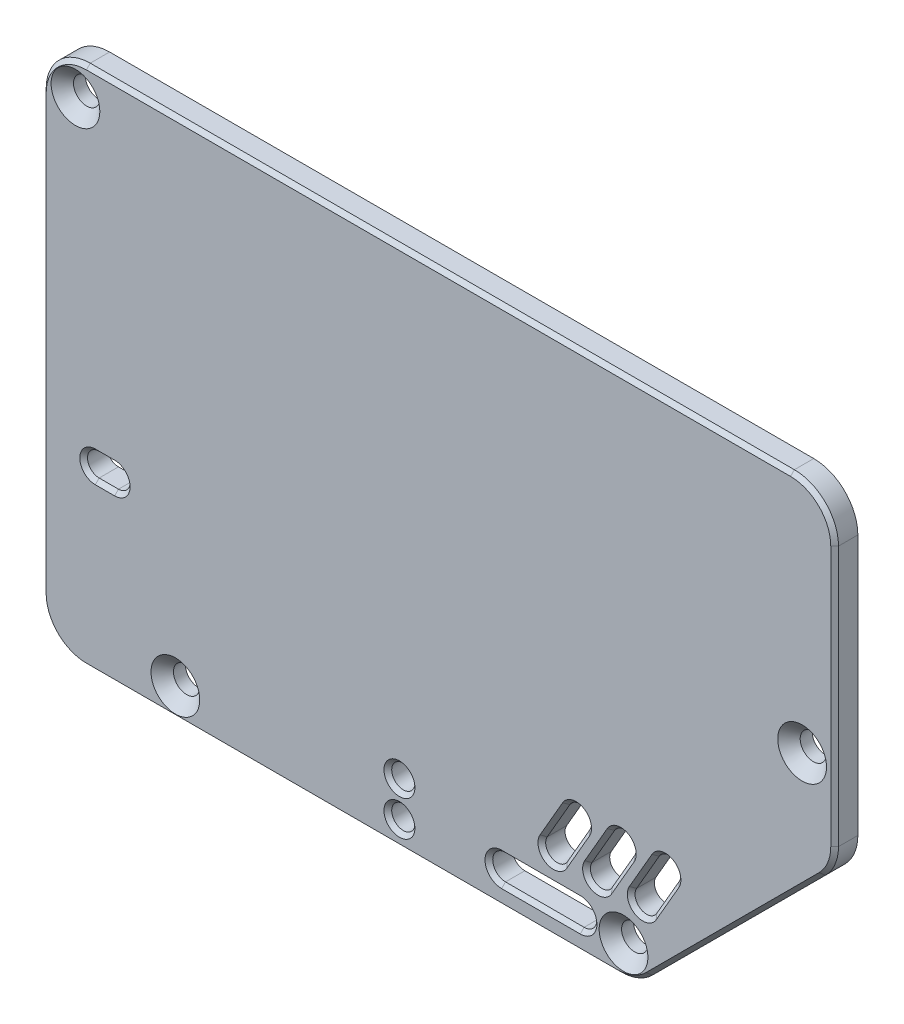
SolidWorks part; units mm, degrees
ref_plane "Front Plane" through (0, 0, 0) normal (0, 0, 1) x (1, 0, 0)
ref_plane "Top Plane" through (0, 0, 0) normal (0, 1, 0) x (1, 0, 0)
ref_plane "Right Plane" through (0, 0, 0) normal (1, 0, 0) x (0, 0, -1)
sketch "Sketch2" plane through (0, 0, 8.62) normal (0, 0, 1) x (1, 0, 0)
  line L0 (4.5, 66.2) -> (95.5, 66.2)
  line L1 (101.2, 60.5) -> (101.2, 26.864)
  line L2 (99.5305, 22.8335) -> (77.1665, 0.4695)
  line L3 (73.136, -1.2) -> (4.5, -1.2)
  line L4 (-1.2, 4.5) -> (-1.2, 60.5)
  line L5 (-1.5, 60.5) -> (-1.5, 4.5) construction
  arc A0 (4.5, -1.2) -> (-1.2, 4.5) centre (4.5, 4.5) cw
  arc A1 (77.1665, 0.4695) -> (73.136, -1.2) centre (73.136, 4.5) cw
  arc A2 (101.2, 26.864) -> (99.5305, 22.8335) centre (95.5, 26.864) cw
  arc A3 (95.5, 66.2) -> (101.2, 60.5) centre (95.5, 60.5) cw
  arc A4 (4.5, 66.2) -> (-1.2, 60.5) centre (4.5, 60.5) ccw
  arc A5 (-1.5, 4.5) -> (4.5, -1.5) centre (4.5, 4.5) ccw construction
  arc A6 (4.5, 66.5) -> (-1.5, 60.5) centre (4.5, 60.5) ccw construction
  arc A7 (101.5, 60.5) -> (95.5, 66.5) centre (95.5, 60.5) ccw construction
  arc A8 (73.136, -1.5) -> (77.3787, 0.2574) centre (73.136, 4.5) ccw construction
  circle A9 centre (3.0858, 61.9142) radius 1.5 construction
  circle A10 centre (16, 2.5) radius 1.5 construction
  circle A11 centre (73.9175, 2.659) radius 1.5 construction
  circle A12 centre (97, 35.5) radius 1.5 construction
  circle A13 centre (16, 2.5) radius 1.35 construction
  arc A14 (101.3205, 25.4074) -> (101.5, 26.864) centre (95.5, 26.864) ccw construction
  circle A15 centre (73.9175, 2.659) radius 1.35 construction
  circle A16 centre (97, 35.5) radius 1.35 construction
  circle A17 centre (3.0858, 61.9142) radius 1.35 construction
  dimension "D1" = 0.3
  dimension "D2" = 3
extrude "Boss-Extrude1" add sketch "Sketch2" along normal blind 3
hole_wizard "CSK for M3 Flat Head Machine Screw1" positions "Sketch4" profile "Sketch5" countersink size "M3" standard "ANSI Metric" end condition through all
sketch "Sketch4" plane through (0, 0, 11.62) normal (0, 0, 1) x (1, 0, 0)
  point P0 (3.0858, 61.9142)
  point P3 (16, 2.5)
  point P6 (73.9175, 2.659)
  point P9 (97, 35.5)
sketch "Sketch5" plane through (3.0858, 61.9142, 11.62) normal (1, 0, 0) x (0, -1, 0)
  line L0 (0, 0) -> (0, 3)
  line L1 (0, 3) -> (1.7, 3)
  line L2 (1.7, 3) -> (1.7, 1.45)
  line L3 (1.7, 1.45) -> (3.15, 0)
  line L5 (3.15, 0) -> (0, 0)
  line L6 (-1.7, 1.45) -> (-3.15, 0) construction
  line L11 (0, -6.35) -> (0, 107.95) construction
  dimension "Thru Hole Dia." = 3.4
  dimension "Thru Hole Depth" = 3
  dimension "Near C'Sink Dia." = 6.3
  dimension "Near C'Sink Angle" = 90
sketch "Sketch6" plane through (0, 0, 11.62) normal (0, 0, 1) x (1, 0, 0)
  line L6 (72.0938, 16.422) -> (72.0938, 14.1605) construction
  line L8 (78.5938, 16.422) -> (65.5938, 16.422) construction
  line L10 (68.326, 3.048) -> (58.166, 3.048) construction
  line L11 (68.326, 1.397) -> (58.166, 1.397)
  line L12 (68.326, 4.699) -> (58.166, 4.699)
  line L13 (72.0938, 7.6835) -> (72.0938, 5.422) construction
  line L14 (65.5938, 5.422) -> (78.5938, 5.422) construction
  arc A4 (68.326, 1.397) -> (68.326, 4.699) centre (68.326, 3.048) ccw
  arc A5 (58.166, 4.699) -> (58.166, 1.397) centre (58.166, 3.048) ccw
  point P26 (63.246, 3.048)
  dimension "D4" = 3.302
extrude "Cut-Extrude1" cut sketch "Sketch6" against normal through all
sketch "Sketch7" plane through (0, 0, 11.62) normal (0, 0, 1) x (1, 0, 0)
  line L1 (19.25, 57.135) -> (67.25, 57.135)
  line L2 (18.615, 56.5) -> (18.615, 20.1)
  line L3 (19.25, 19.465) -> (67.25, 19.465)
  line L4 (67.885, 56.5) -> (67.885, 20.1)
  arc A4 (67.25, 57.135) -> (67.885, 56.5) centre (67.25, 56.5) cw
  arc A5 (67.25, 19.465) -> (67.885, 20.1) centre (67.25, 20.1) ccw
  arc A6 (18.615, 20.1) -> (19.25, 19.465) centre (19.25, 20.1) ccw
  arc A7 (19.25, 57.135) -> (18.615, 56.5) centre (19.25, 56.5) ccw
  dimension "D2" = 0.635
split line "Split Line1" [suppressed]
sketch "Sketch8" plane through (0, 0, 11.62) normal (0, 0, 1) x (1, 0, 0)
  circle A0 centre (44.958, 2.54) radius 1
  circle A1 centre (44.958, 6.096) radius 1
  dimension "D1" = 2
extrude "Cut-Extrude2" cut sketch "Sketch8" against normal blind 10
sketch "Sketch9" plane through (0, 0, 11.62) normal (0, 0, 1) x (1, 0, 0)
  line L0 (65.0938, 10.922) -> (68.5938, 10.922) construction
  line L1 (68.5938, 10.922) -> (72.0938, 10.922) construction
  line L2 (72.0938, 10.922) -> (75.5938, 10.922) construction
  line L3 (75.5938, 10.922) -> (79.0938, 10.922) construction
  line L4 (66.8438, 13.9531) -> (66.8438, 7.8909) construction
  line L5 (65.0938, 10.922) -> (66.8438, 7.8909) construction
  line L6 (70.3438, 7.8909) -> (70.3438, 13.9531) construction
  line L7 (72.0938, 15.272) -> (72.0938, 6.572) construction
  line L8 (73.8438, 13.9531) -> (73.8438, 7.8909) construction
  line L9 (75.8938, 15.272) -> (68.2938, 15.272) construction
  line L10 (77.3438, 7.8909) -> (77.3438, 13.9531) construction
  line L11 (68.2938, 6.572) -> (75.8938, 6.572) construction
  circle A0 centre (65.0938, 10.922) radius 1
  circle A1 centre (68.5938, 10.922) radius 1
  circle A2 centre (72.0938, 10.922) radius 1
  circle A3 centre (75.5938, 10.922) radius 1
  circle A4 centre (79.0938, 10.922) radius 1
  circle A5 centre (66.8438, 13.9531) radius 1
  circle A6 centre (70.3438, 13.9531) radius 1
  circle A7 centre (73.8438, 13.9531) radius 1
  circle A8 centre (77.3438, 13.9531) radius 1
  circle A9 centre (66.8438, 7.8909) radius 1
  circle A10 centre (70.3438, 7.8909) radius 1
  circle A11 centre (73.8438, 7.8909) radius 1
  circle A12 centre (77.3438, 7.8909) radius 1
  circle A13 centre (44.958, 6.096) radius 1 construction
  point P18 (66.8438, 10.922)
  point P19 (70.3438, 10.922)
  point P20 (73.8438, 10.922)
  point P21 (77.3438, 10.922)
  dimension "D1" = 3.5
extrude "Cut-Extrude3" [suppressed] cut sketch "Sketch9" against normal blind 10
sketch "Sketch10" plane through (0, 0, 11.62) normal (0, 0, 1) x (1, 0, 0)
  line L0 (5.1479, 21.844) -> (8.6479, 21.844) construction
  line L1 (6.8979, 23.4191) -> (6.8979, 20.2689) construction
  line L2 (9.3459, 23.4191) -> (4.4498, 23.4191) construction
  line L3 (4.4498, 20.2689) -> (9.3459, 20.2689) construction
  circle A0 centre (5.1479, 21.844) radius 1
  circle A1 centre (8.6479, 21.844) radius 1
  circle A2 centre (44.958, 6.096) radius 1 construction
  point P12 (6.8979, 21.844)
  dimension "D1" = 3.5
extrude "Cut-Extrude4" cut sketch "Sketch10" against normal blind 10
chamfer "Chamfer1" [suppressed] distance 0.5 angle 45
sketch "Sketch12" plane through (0, 0, 11.62) normal (0, 0, 1) x (1, 0, 0)
  line L0 (5.6479, 21.844) -> (8.1479, 21.844) construction
  line L1 (5.6479, 23.344) -> (8.1479, 23.344)
  line L2 (5.6479, 20.344) -> (8.1479, 20.344)
  line L3 (44.958, 6.596) -> (44.958, 2.04) construction
  line L4 (42.6658, 5.096) -> (46.9218, 5.096) construction
  line L5 (46.9218, 3.54) -> (42.9064, 3.54) construction
  line L6 (70.6325, 8.3909) -> (73.5552, 13.4531) construction
  line L7 (69.3335, 9.1409) -> (72.2561, 14.2031)
  line L8 (71.9315, 7.6409) -> (74.8542, 12.7031)
  line L9 (66.658, 6.8909) -> (75.9903, 6.8909) construction
  line L10 (71.007, 14.9531) -> (76.3222, 14.9531) construction
  line L11 (64.859, 8.3909) -> (67.7817, 13.4531) construction
  line L12 (63.56, 9.1409) -> (66.4826, 14.2031)
  line L13 (66.158, 7.6409) -> (69.0807, 12.7031)
  line L14 (76.406, 8.3909) -> (79.3287, 13.4531) construction
  line L15 (75.107, 9.1409) -> (78.0296, 14.2031)
  line L16 (77.7051, 7.6409) -> (80.6277, 12.7031)
  arc A0 (5.6479, 23.344) -> (5.6479, 20.344) centre (5.6479, 21.844) ccw
  arc A1 (8.1479, 20.344) -> (8.1479, 23.344) centre (8.1479, 21.844) ccw
  circle A2 centre (5.1479, 21.844) radius 1 construction
  circle A3 centre (8.6479, 21.844) radius 1 construction
  circle A4 centre (44.958, 6.596) radius 1.5
  circle A5 centre (44.958, 2.04) radius 1.5
  circle A6 centre (73.8438, 13.9531) radius 1 construction
  circle A7 centre (44.958, 6.096) radius 1 construction
  circle A8 centre (44.958, 2.54) radius 1 construction
  arc A9 (69.3335, 9.1409) -> (71.9315, 7.6409) centre (70.6325, 8.3909) ccw
  arc A10 (74.8542, 12.7031) -> (72.2561, 14.2031) centre (73.5552, 13.4531) ccw
  arc A11 (63.56, 9.1409) -> (66.158, 7.6409) centre (64.859, 8.3909) ccw
  circle A12 centre (70.3438, 7.8909) radius 1 construction
  arc A13 (69.0807, 12.7031) -> (66.4826, 14.2031) centre (67.7817, 13.4531) ccw
  arc A14 (75.107, 9.1409) -> (77.7051, 7.6409) centre (76.406, 8.3909) ccw
  arc A15 (80.6277, 12.7031) -> (78.0296, 14.2031) centre (79.3287, 13.4531) ccw
  point P2 (6.8979, 21.844)
  point P7 (4.1479, 21.844)
  point P8 (4.1479, 21.844)
  point P11 (9.6479, 21.844)
  point P12 (9.6479, 21.844)
  point P13 (5.1479, 21.844)
  point P21 (44.958, 6.096)
  point P33 (72.0938, 10.922)
  point P50 (66.3203, 10.922)
  point P55 (77.8673, 10.922)
  dimension "D2" = 3
  dimension "D1" = 3
  dimension "D3" = 3
  dimension "D4" = 2
  dimension "D5" = 2
extrude "Cut-Extrude5" cut sketch "Sketch12" against normal blind 10
chamfer "Chamfer2" distance 0.5 angle 45 32 edges at (63.246, 1.397, 11.62) (69.977, 3.048, 11.62) (56.515, 3.048, 11.62) (63.246, 4.699, 11.62) (79.1664, 10.172, 11.62) (80.0787, 14.7521, 11.62) (75.656, 7.0919, 11.62) (76.5683, 11.672, 11.62) (73.3929, 10.172, 11.62) (74.3052, 14.7521, 11.62) (69.8825, 7.0919, 11.62) (70.7948, 11.672, 11.62) (65.0213, 11.672, 11.62) (64.109, 7.0919, 11.62) (68.5317, 14.7521, 11.62) (67.6194, 10.172, 11.62) (46.458, 2.04, 11.62) (46.458, 6.596, 11.62) (6.8979, 23.344, 11.62) (4.1479, 21.844, 11.62) (9.6479, 21.844, 11.62) (6.8979, 20.344, 11.62) (100.7661, 24.6827, 11.62) (101.2, 43.682, 11.62) (88.3485, 11.6515, 11.62) (99.5305, 64.5305, 11.62) (75.3173, -0.7661, 11.62) (50, 66.2, 11.62) (38.818, -1.2, 11.62) (0.4695, 64.5305, 11.62) (0.4695, 0.4695, 11.62) (-1.2, 32.5, 11.62)
